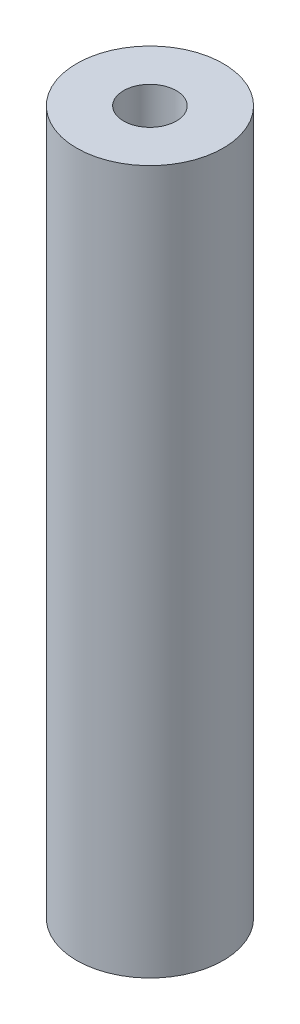
SolidWorks part; units mm, degrees
ref_plane "前视基准面" through (0, 0, 0) normal (0, 0, 1) x (1, 0, 0)
ref_plane "上视基准面" through (0, 0, 0) normal (0, 1, 0) x (1, 0, 0)
ref_plane "右视基准面" through (0, 0, 0) normal (1, 0, 0) x (0, 0, -1)
other "Configuration Table"
sketch "草图2" plane through (0, 0, 0) normal (0, 1, 0) x (1, 0, 0)
  circle A18 centre (0, 0) radius 2.5
  circle A19 centre (0, 0) radius 0.9
  dimension "D1" = 1.8
  dimension "D2" = 5
extrude "凸台-拉伸1" add sketch "草图2" along normal blind 24
